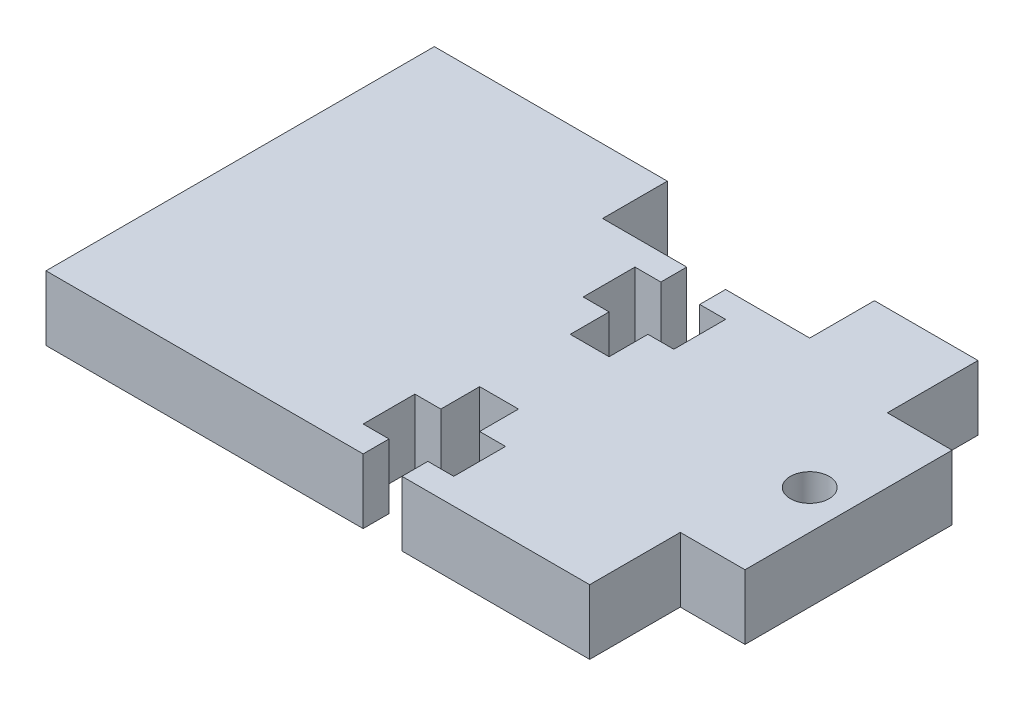
SolidWorks part; units mm, degrees
material "Trupan"
ref_plane "Alzado" through (0, 0, 0) normal (0, 0, 1) x (1, 0, 0)
ref_plane "Planta" through (0, 0, 0) normal (0, 1, 0) x (1, 0, 0)
ref_plane "Vista lateral" through (0, 0, 0) normal (1, 0, 0) x (0, 0, -1)
sketch "Croquis1" plane through (0, 0, 0) normal (0, 1, 0) x (1, 0, 0)
  line L1 (16, -15) -> (-16, -15)
  line L2 (16, -15) -> (16, 15)
  line L3 (16, 15) -> (-16, 15)
  line L4 (-16, -15) -> (-16, 15)
  line L5 (16, -15) -> (-16, 15) construction
  line L6 (16, 15) -> (-16, -15) construction
  point P0 (0, 0)
  dimension "D1" = 32
  dimension "D2" = 30
extrude "Saliente-Extruir1" add sketch "Croquis1" along normal blind 5
sketch "Croquis2" plane through (0, 5, 0) normal (0, 1, 0) x (1, 0, 0)
  line L0 (0, 15) -> (0, -15) construction
  line L1 (-8, 15) -> (8, 15)
  line L2 (8, 15) -> (8, 10)
  line L3 (8, 10) -> (1.5, 10)
  line L4 (1.5, 10) -> (1.5, 8)
  line L5 (1.5, 8) -> (3.5, 8)
  line L6 (3.5, 8) -> (3.5, 4)
  line L7 (3.5, 4) -> (1.5, 4)
  line L8 (1.5, 4) -> (1.5, 1)
  line L9 (1.5, 1) -> (-1.5, 1)
  line L10 (-1.5, 4) -> (-1.5, 1)
  line L11 (-3.5, 4) -> (-1.5, 4)
  line L12 (-1.5, 8) -> (-3.5, 8)
  line L13 (-3.5, 8) -> (-3.5, 4)
  line L14 (-1.5, 10) -> (-1.5, 8)
  line L15 (-8, 10) -> (-1.5, 10)
  line L16 (-8, 15) -> (-8, 10)
  line L17 (16, 15) -> (-16, 15) construction
  point P12 (0, 1)
  dimension "D1" = 8
  dimension "D2" = 5
  dimension "D3" = 6.5
  dimension "D4" = 2
  dimension "D5" = 2
  dimension "D6" = 4
  dimension "D7" = 2
  dimension "D8" = 3
  dimension "D9" = 0
extrude "Cortar-Extruir1" cut sketch "Croquis2" against normal through all
sketch "Croquis3" plane through (0, 5, 0) normal (0, 1, 0) x (1, 0, 0)
  line L0 (0, -15) -> (0, 0) construction
  line L1 (-16, -15) -> (16, -15) construction
  line L2 (0, -15) -> (0, 15.5179) construction
  line L3 (1.5, -15) -> (1.5, -13)
  line L4 (1.5, -13) -> (3.5, -13)
  line L5 (3.5, -13) -> (3.5, -9)
  line L6 (3.5, -9) -> (1.5, -9)
  line L7 (1.5, -9) -> (1.5, -6)
  line L8 (1.5, -6) -> (-1.5, -6)
  line L9 (1.5, -15) -> (-1.5, -15)
  line L10 (-1.5, -9) -> (-1.5, -6)
  line L11 (-3.5, -9) -> (-1.5, -9)
  line L12 (-3.5, -13) -> (-3.5, -9)
  line L13 (-1.5, -13) -> (-3.5, -13)
  line L14 (-1.5, -15) -> (-1.5, -13)
  point P15 (0, -6)
  dimension "D1" = 2
  dimension "D2" = 2
  dimension "D3" = 4
  dimension "D4" = 2
  dimension "D5" = 3
  dimension "D6" = 1.5
  dimension "D7" = 0
extrude "Cortar-Extruir2" cut sketch "Croquis3" against normal through all
sketch "Croquis4" plane through (0, 5, 0) normal (0, 1, 0) x (1, 0, 0)
  line L0 (16, -15) -> (16, 15) construction
  line L1 (21, -8) -> (11, -8)
  line L2 (21, -8) -> (21, 8)
  line L3 (21, 8) -> (11, 8)
  line L4 (11, -8) -> (11, 8)
  line L5 (21, -8) -> (11, 8) construction
  line L6 (21, 8) -> (11, -8) construction
  point P0 (16, 0)
  dimension "D1" = 16
  dimension "D2" = 5
extrude "Saliente-Extruir2" add sketch "Croquis4" against normal up to surface (5 mm away) up to face at (0, 0, 0.3125)
sketch "Croquis5" plane through (0, 5, 0) normal (0, 1, 0) x (1, 0, 0)
  line L0 (21, -8) -> (21, 8) construction
  line L1 (21, 8) -> (16, 8) construction
  circle A0 centre (18, 0) radius 1.5
  dimension "D2" = 3
  dimension "D1" = 3
  dimension "D3" = 8
extrude "Cortar-Extruir3" cut sketch "Croquis5" against normal through all
sketch "Croquis6" plane through (0, 5, 0) normal (0, 1, 0) x (1, 0, 0)
  line L1 (-16, 15) -> (-26, 15)
  line L2 (-16, 15) -> (-16, -15)
  line L3 (-16, -15) -> (-26, -15)
  line L4 (-26, 15) -> (-26, -15)
  dimension "D1" = 10
extrude "Saliente-Extruir3" add sketch "Croquis6" against normal blind 5
